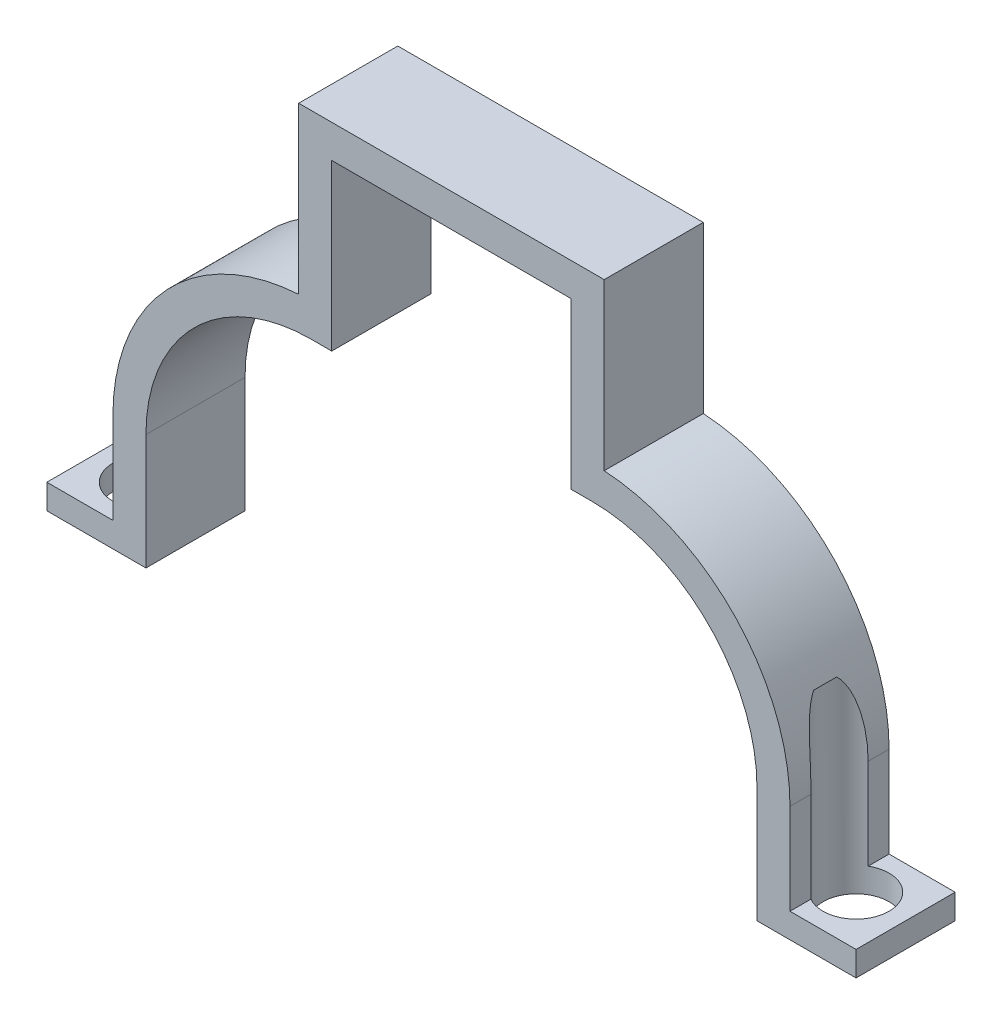
SolidWorks part; units mm, degrees
ref_plane "정면도" through (0, 0, 0) normal (0, 0, 1) x (1, 0, 0)
ref_plane "평면도" through (0, 0, 0) normal (0, 1, 0) x (1, 0, 0)
ref_plane "우측면도" through (0, 0, 0) normal (1, 0, 0) x (0, 0, -1)
sketch "스케치1" plane through (0, 0, 0) normal (0, 0, 1) x (1, 0, 0)
  line L0 (31.75, 18.5) -> (33, 18.5)
  line L1 (17.25, 28.5) -> (31.75, 28.5)
  line L2 (17.25, 28.5) -> (17.25, 18.5)
  line L3 (49, 3) -> (45, 3)
  line L4 (49, 1.5) -> (49, 3)
  line L5 (45, 3) -> (45, 8.5)
  line L6 (33.75, 30.5) -> (33.75, 20.4765)
  line L7 (49, 1.5) -> (43, 1.5)
  line L8 (43, 8.5) -> (43, 1.5)
  line L9 (6, 8.5) -> (6, 1.5)
  line L10 (0, 1.5) -> (6, 1.5)
  line L11 (31.75, 28.5) -> (31.75, 18.5)
  line L13 (15.25, 30.5) -> (33.75, 30.5)
  line L14 (15.25, 30.5) -> (15.25, 20.4765)
  line L15 (4, 3) -> (4, 8.5)
  line L16 (15.25, 30.5) -> (15.25, 18.5) construction
  line L17 (0, 1.5) -> (0, 3)
  line L18 (0, 3) -> (4, 3)
  line L19 (24.5, 30.5) -> (24.5, 0) construction
  line L20 (15.25, 30.5) -> (33.75, 30.5) construction
  line L21 (17.25, 28.5) -> (31.75, 28.5) construction
  line L22 (17.25, 18.5) -> (16, 18.5)
  line L23 (33.75, 30.5) -> (33.75, 18.5) construction
  line L24 (31.75, 28.5) -> (31.75, 18.5) construction
  arc A0 (33.75, 20.4765) -> (45, 8.5) centre (33, 8.5) cw
  arc A1 (16, 18.5) -> (6, 8.5) centre (16, 8.5) ccw
  arc A2 (15.25, 20.4765) -> (4, 8.5) centre (16, 8.5) ccw
  arc A3 (33, 18.5) -> (43, 8.5) centre (33, 8.5) cw
  point P10 (24.5, 28.5)
  dimension "D2" = 2
  dimension "D3" = 2
  dimension "D4" = 1.5
extrude "보스-돌출1" add sketch "스케치1" along normal blind 6
sketch "스케치2" plane through (0, 3, 0) normal (0, 1, 0) x (1, 0, 0)
  line L0 (43, -6) -> (43, 0) construction
  line L1 (43, -6) -> (43, 0) construction
  line L3 (43, -6) -> (49, 0) construction
  line L4 (49, -6) -> (43, 0) construction
  line L5 (6, -6) -> (6, 0) construction
  line L6 (6, -6) -> (6, 0) construction
  line L7 (6, 0) -> (0, -6) construction
  line L8 (6, -6) -> (0, 0) construction
  circle A0 centre (46, -3) radius 2
  circle A1 centre (3, -3) radius 2
  line M4 (45, 0) -> (45, -6)
  dimension "D1" = 4
  dimension "D2" = 4
extrude "컷-돌출1" cut sketch "스케치2" against normal blind 10 and the other way blind 10 contours A0 M4 | A0 M4 | A1
